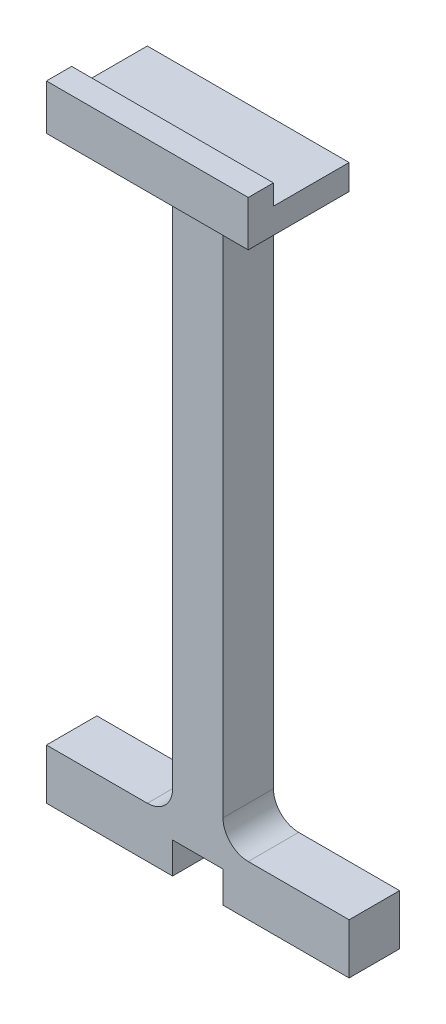
SolidWorks part; units mm, degrees
ref_plane "Front Plane" through (0, 0, 0) normal (0, 0, 1) x (1, 0, 0)
ref_plane "Top Plane" through (0, 0, 0) normal (0, 1, 0) x (1, 0, 0)
ref_plane "Right Plane" through (0, 0, 0) normal (1, 0, 0) x (0, 0, -1)
sketch "Sketch1" plane through (0, 0, 0) normal (0, 0, 1) x (1, 0, 0)
  line L0 (5, -57.5) -> (30, -57.5)
  line L2 (-5, 57.5) -> (-5, -57.5)
  line L4 (5, 57.5) -> (5, -57.5)
  line L5 (0, -67.5) -> (0, 62.5) construction
  line L6 (-5, 0) -> (5, 0) construction
  line L7 (-30, -67.5) -> (30, -67.5)
  line L8 (-30, -67.5) -> (-30, -57.5)
  line L9 (-30, -57.5) -> (-5, -57.5)
  line L10 (30, -67.5) -> (30, -57.5)
  line L11 (5, 57.5) -> (20, 57.5)
  line L12 (-20, 57.5) -> (-5, 57.5)
  line L13 (-20, 57.5) -> (-20, 62.5)
  line L14 (-20, 62.5) -> (20, 62.5)
  line L15 (20, 57.5) -> (20, 62.5)
  point P0 (0, 0)
  point P8 (0, -67.5)
  point P13 (0, 62.5)
  point P14 (-43.169, -53.4674)
  point P15 (7.1197, -57.5)
  point P16 (0, 62.5)
  point P17 (0, -67.5)
  dimension "D1" = 130
  dimension "D2" = 10
  dimension "D3" = 10
  dimension "D4" = 5
  dimension "D5" = 40
  dimension "D6" = 60
extrude "Boss-Extrude1" add sketch "Sketch1" along normal mid plane 10
sketch "Sketch3" plane through (0, 62.5, 0) normal (0, 1, 0) x (1, 0, 0)
  line L1 (-20, -5) -> (20, -5)
  line L2 (-20, -5) -> (-20, -15)
  line L3 (-20, -15) -> (20, -15)
  line L4 (20, -5) -> (20, -15)
  dimension "D1" = 10
extrude "Boss-Extrude2" add sketch "Sketch3" against normal blind 5
sketch "Sketch4" plane through (0, 62.5, 0) normal (0, 1, 0) x (1, 0, 0)
  line L0 (20, -15) -> (20, 5) construction
  line L1 (-20, -15) -> (20, -15)
  line L2 (-20, -15) -> (-20, -10)
  line L3 (-20, -10) -> (20, -10)
  line L4 (20, -15) -> (20, -10)
  dimension "D1" = 5
extrude "Boss-Extrude3" add sketch "Sketch4" along normal blind 4
sketch "Sketch6" plane through (0, 0, 0) normal (0, 0, 1) x (1, 0, 0)
  line L0 (-30, -67.5) -> (30, -67.5) construction
  line L1 (5, -57.5) -> (-5, -57.5)
  line L2 (5, -57.5) -> (5, -67.5)
  line L3 (5, -67.5) -> (-5, -67.5)
  line L4 (-5, -57.5) -> (-5, -67.5)
  point P7 (-3.0301, -57.5)
extrude "Boss-Extrude4" [suppressed] add sketch "Sketch6" along normal mid plane 50
sketch "Sketch7" plane through (0, 0, 5) normal (0, 0, 1) x (1, 0, 0)
  line L0 (-30, -67.5) -> (30, -67.5) construction
  line L1 (5, -67.5) -> (-5, -67.5)
  line L2 (5, -67.5) -> (5, -61.3)
  line L3 (5, -61.3) -> (-5, -61.3)
  line L4 (-5, -67.5) -> (-5, -61.3)
  line L5 (5, -57.5) -> (5, 57.5) construction
  line L6 (-5, 57.5) -> (-5, -57.5) construction
  dimension "D1" = 6.2
extrude "Cut-Extrude1" cut sketch "Sketch7" against normal through all
sketch "Sketch8" plane through (0, -61.3, 0) normal (0, -1, 0) x (1, 0, 0)
  circle A0 centre (0, 0) radius 2
  dimension "D1" = 4
extrude "Cut-Extrude2" cut sketch "Sketch8" against normal blind 6
fillet "Fillet3" radius 5 5 edges at (5, -57.5, 0) (-5, -57.5, 0) (-5, 57.5, 0) (0, 57.5, 5) (5, 57.5, 0)
